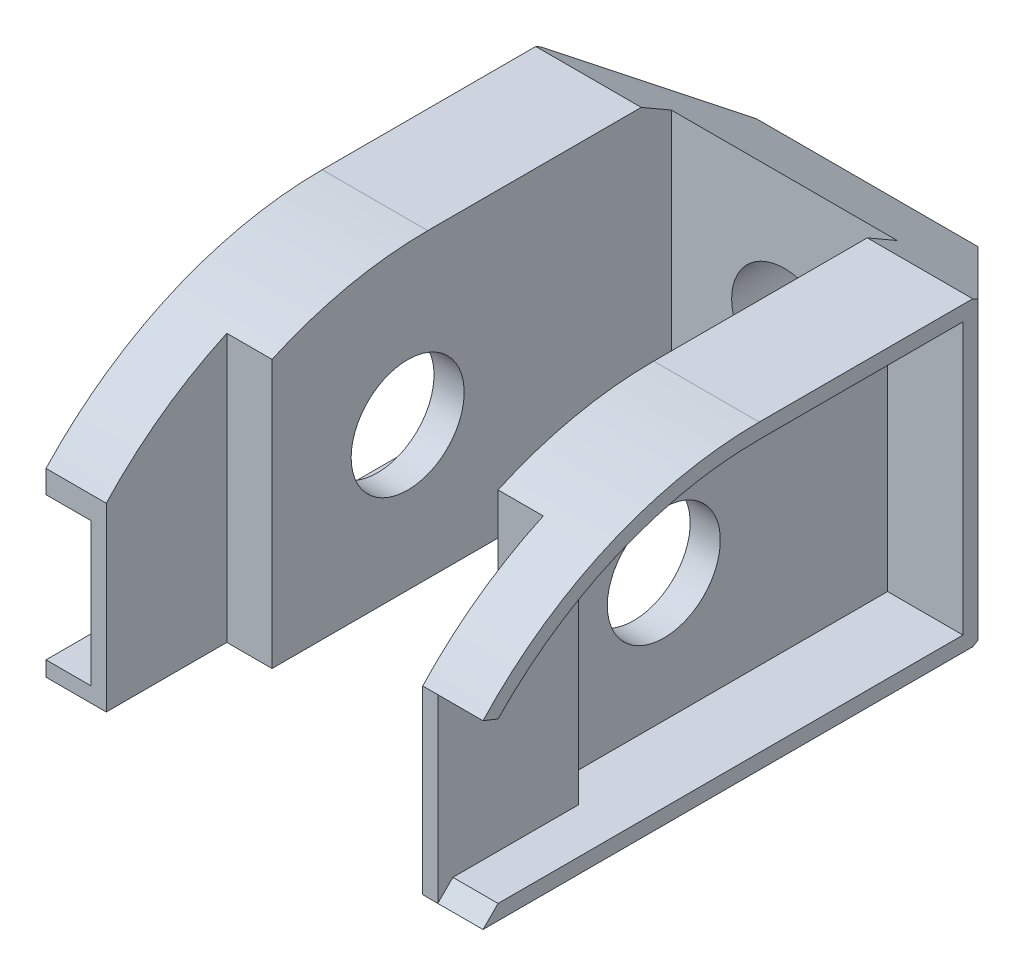
SolidWorks part; units mm, degrees
material "1060 Alloy"
ref_plane "Front Plane" through (0, 0, 0) normal (0, 0, 1) x (1, 0, 0)
ref_plane "Top Plane" through (0, 0, 0) normal (0, 1, 0) x (1, 0, 0)
ref_plane "Right Plane" through (0, 0, 0) normal (1, 0, 0) x (0, 0, -1)
sketch "Sketch1" plane through (0, 0, 0) normal (1, 0, 0) x (0, 0, -1)
  line L0 (0, 0) -> (65, 0)
  line L1 (0, 0) -> (0, 24)
  line L2 (65, 0) -> (80, 8.6603)
  line L3 (80, 8.6603) -> (80, 31.3397)
  line L4 (80, 31.3397) -> (65, 40)
  line L5 (65, 40) -> (36.6606, 40)
  arc A0 (36.6606, 40) -> (0, 24) centre (36.6606, -10) ccw
  circle A1 centre (34, 19) radius 7.5
  dimension "D7" = 50
  dimension "D9" = 15
  dimension "D1" = 65
  dimension "D2" = 24
  dimension "D3" = 15
  dimension "D4" = 30
  dimension "D5" = 15
  dimension "D6" = 30
  dimension "D8" = 40
  dimension "D10" = 19
  dimension "D11" = 31
extrude "Boss-Extrude1" add sketch "Sketch1" along normal blind 58
sketch "Sketch3" plane through (0, 0, 0) normal (0, 1, 0) x (1, 0, 0)
  line L0 (29, 80.0246) -> (29, 0.0246) construction
  line L3 (58, 0) -> (0, 0) construction
  line L4 (0, 36.6606) -> (0, 0) construction
  line L5 (58, 0) -> (58, 36.6606) construction
  line L6 (58, 65) -> (58, 36.6606) construction
  line L7 (58, 36.6606) -> (0, 36.6606) construction
  line L8 (0, 65) -> (0, 36.6606) construction
  line L9 (58, 65) -> (0, 65) construction
  line L10 (0, 80) -> (0, 65) construction
  line L11 (58, 80) -> (0, 80) construction
  line L12 (58, 0) -> (0, 0)
  line L13 (0, 36.6606) -> (0, 0)
  line L14 (58, 0) -> (58, 36.6606)
  line L15 (58, 65) -> (58, 36.6606)
  line L16 (58, 36.6606) -> (0, 36.6606)
  line L17 (0, 65) -> (0, 36.6606)
  line L18 (58, 65) -> (0, 65)
  line L19 (0, 80) -> (0, 65)
  line L20 (58, 80) -> (0, 80)
  line L22 (14, 69) -> (44, 69)
  line L23 (14, 69) -> (14, 16)
  line L24 (14, 16) -> (44, 16)
  line L25 (44, 69) -> (44, 16)
  line L26 (14, 69) -> (44, 16) construction
  line L27 (14, 16) -> (44, 69) construction
  point P4 (29, 42.5)
  dimension "D1" = 11
  dimension "D2" = 16
  dimension "D3" = 16
  dimension "D4" = 14
  dimension "D5" = 14
extrude "Cut-Extrude1" cut sketch "Sketch3" against normal blind 10 and the other way through all contours L25 L24 L23 L22
sketch "Sketch5" plane through (0, 0, 0) normal (0, 1, 0) x (1, 0, 0)
  line L0 (29, 80) -> (29, 0) construction
  line L1 (58, 80) -> (0, 80) construction
  line L2 (58, 0) -> (0, 0) construction
  line L3 (58, 65) -> (58, 36.6606) construction
  line L5 (44, 36.6606) -> (44, 16) construction
  line L6 (44, 65) -> (44, 36.6606) construction
  line L7 (58, 36.6606) -> (44, 36.6606) construction
  line L9 (14, 16) -> (14, 36.6606) construction
  line L10 (0, 36.6606) -> (0, 0) construction
  line L11 (14, 36.6606) -> (0, 36.6606) construction
  line L12 (0, 65) -> (0, 36.6606) construction
  line L13 (14, 65) -> (14, 36.6606) construction
  line L14 (14, 69) -> (14, 65) construction
  line L15 (44, 69) -> (44, 65) construction
  line L16 (58, 65) -> (44, 65) construction
  line L17 (58, 80) -> (58, 65) construction
  line L18 (0, 80) -> (0, 65) construction
  line L19 (14, 65) -> (0, 65) construction
  line L20 (14, 69) -> (44, 69) construction
  line L21 (58, 65) -> (58, 36.6606)
  line L22 (58, 16) -> (58, 0)
  line L23 (44, 36.6606) -> (44, 16)
  line L24 (44, 65) -> (44, 36.6606)
  line L25 (58, 36.6606) -> (44, 36.6606)
  line L26 (8, 16) -> (44, 16)
  line L27 (14, 16) -> (14, 36.6606)
  line L28 (0, 36.6606) -> (0, 0)
  line L29 (50, 16) -> (58, 16)
  line L30 (14, 36.6606) -> (0, 36.6606)
  line L31 (0, 65) -> (0, 36.6606)
  line L32 (14, 65) -> (14, 36.6606)
  line L33 (14, 69) -> (14, 65)
  line L34 (44, 69) -> (44, 65)
  line L35 (58, 65) -> (44, 65)
  line L36 (58, 80) -> (58, 65)
  line L37 (0, 80) -> (0, 65)
  line L38 (14, 65) -> (0, 65)
  line L39 (14, 69) -> (44, 69)
  line L40 (58, 80) -> (0, 80)
  line L41 (58, 0) -> (50, 0)
  line L42 (50, 0) -> (50, 16)
  line L43 (50, 16) -> (44, 16)
  line L44 (50, 0) -> (58, 0)
  line L45 (58, 16) -> (58, 0)
  line L46 (0, 16) -> (0, 0)
  line L47 (0, 0) -> (8, 0)
  line L48 (8, 0) -> (8, 16)
  line L49 (8, 16) -> (0, 16)
  line L50 (8, 0) -> (50, 0)
  dimension "D1" = 8
  dimension "D2" = 6
  dimension "D3" = 16
extrude "Cut-Extrude3" cut sketch "Sketch5" against normal through all and the other way up to next contours L0 L26 L48 L50 | L26 L0 L50 L42 L43
sketch "Sketch7" plane through (0, 0, 0) normal (0, 1, 0) x (1, 0, 0)
  line L0 (29, 80) -> (29, 69) construction
  line L1 (0, 65) -> (0, 36.6606) construction
  line L2 (58, 80) -> (0, 80) construction
  line L3 (14, 69) -> (44, 69) construction
  line L4 (0, 65.6967) -> (14.3033, 80)
  line L5 (0, 80) -> (0, 65) construction
  line L6 (14.3033, 80) -> (0, 80)
  line L7 (0, 80) -> (0, 65.6967)
  line L8 (58, 65.6967) -> (43.6967, 80)
  line L9 (43.6967, 80) -> (58, 80)
  line L10 (58, 80) -> (58, 65.6967)
  dimension "D1" = 45
  dimension "D2" = 14.3033
extrude "Cut-Extrude4" cut sketch "Sketch7" along normal through all contours L7 L4 L6 | L8 L9 L10
sketch "Sketch8" plane through (0, 0, -80) normal (0, 0, -1) x (-1, 0, 0)
  line L0 (-29, 31.3397) -> (-29, 8.6603) construction
  line L1 (-43.6967, 31.3397) -> (-14.3033, 31.3397) construction
  line L2 (-43.6967, 8.6603) -> (-14.3033, 8.6603) construction
  circle A1 centre (-29, 20) radius 7
  dimension "D1" = 14
extrude "Cut-Extrude5" cut sketch "Sketch8" against normal through all
sketch "Sketch10" plane through (0, 0, 0) normal (-1, 0, 0) x (0, 0, 1)
  line L8 (-63.6967, 39.5978) -> (-63.6967, 0.4022)
  line L9 (-63.6967, 38) -> (-63.6967, 2)
  line L34 (-65, 38) -> (-36.6606, 38)
  line L35 (-63.6967, 38) -> (-36.6606, 38)
  line L37 (0, 2) -> (-65, 2)
  line L38 (0, 2) -> (-63.6967, 2)
  line L39 (0, 24) -> (0, 0) construction
  line L40 (0, 20.9839) -> (0, 24)
  line L41 (0, 2) -> (0, 0)
  line L42 (0, 0) -> (-65, 0)
  line L43 (-65, 0) -> (-65.6967, 0.4022)
  line L44 (-65.6967, 0.4022) -> (-65.6967, 39.5978)
  line L45 (-65.6967, 39.5978) -> (-65, 40)
  line L46 (-65, 40) -> (-36.6606, 40)
  line L47 (0, 20.9839) -> (0, 2)
  arc A13 (-36.6606, 40) -> (0, 24) centre (-36.6606, -10) cw
  arc A14 (-1.4664, 22.64) -> (-36.6606, 38) centre (-36.6606, -10) ccw
  arc A15 (0, 20.9839) -> (-36.6606, 38) centre (-36.6606, -10) ccw
  circle M13 centre (-34, 19) radius 7.5
  line M17 (0, 0) -> (0, 24)
  dimension "D1" = 2
  dimension "D2" = 2
  dimension "D3" = 2
  dimension "D4" = 2
extrude "Cut-Extrude6" cut sketch "Sketch10" against normal blind 6 contours A15 L35 L9 L38 M17 M13
sketch "Sketch11" plane through (6, 0, 0) normal (-1, 0, 0) x (0, 0, 1)
  line L3 (-63.6967, 2) -> (-63.6967, 38)
  line L6 (-18.6967, 34.5118) -> (-18.6967, 2)
  line L7 (0, 2) -> (-63.6967, 2) construction
  line L8 (-18.6967, 2) -> (-63.6967, 2)
  line L9 (-63.6967, 38) -> (-36.6606, 38)
  arc A0 (0, 20.9839) -> (-36.6606, 38) centre (-36.6606, -10) ccw construction
  arc A1 (-36.6606, 38) -> (-18.6967, 34.5118) centre (-36.6606, -10) cw
  dimension "D1" = 45
extrude "Cut-Extrude7" cut sketch "Sketch11" against normal blind 4
sketch "Sketch12" plane through (58, 0, 0) normal (1, 0, 0) x (0, 0, -1)
  line L6 (0, 24) -> (2, 23.2061)
  line L7 (36.6606, 40) -> (65, 40)
  line L8 (65, 40) -> (36.6606, 40) construction
  line L10 (65.6967, 39.5978) -> (65.6967, 0.4022)
  line L11 (65.6967, 0.4022) -> (65, 0)
  line L12 (63.6967, 2) -> (63.6967, 38)
  line L13 (63.6967, 38) -> (36.6606, 38)
  line L14 (2, 23.2061) -> (2, 2)
  line L15 (2, 2) -> (63.6967, 2)
  line L16 (63.6967, 2) -> (63.6967, 38)
  line L17 (63.6967, 38) -> (36.6606, 38)
  line L19 (2, 2) -> (63.6967, 2)
  line L20 (65, 0) -> (0, 0)
  line L21 (0, 0) -> (0, 24)
  line L22 (65, 40) -> (65.6967, 39.5978)
  line L23 (2, 2) -> (0, 0)
  arc A1 (0, 24) -> (36.6606, 40) centre (36.6606, -10) cw
  arc A2 (36.6606, 38) -> (2, 23.2061) centre (36.6606, -10) ccw
  arc A3 (36.6606, 38) -> (2, 23.2061) centre (36.6606, -10) ccw
  line M17 (0, 24) -> (0, 0)
  circle M20 centre (34, 19) radius 7.5
  dimension "D2" = 210
  dimension "D1" = 2
extrude "Cut-Extrude9" cut sketch "Sketch12" against normal blind 6 contours L17 A3 L6 L23 L19 L16 M17 M20
sketch "Sketch13" plane through (52, 0, 0) normal (1, 0, 0) x (0, 0, -1)
  line L0 (18.6967, 34.5118) -> (18.6967, 2)
  line L2 (2, 2) -> (63.6967, 2) construction
  line L3 (18.6967, 2) -> (63.6967, 2)
  line L4 (63.6967, 2) -> (63.6967, 38)
  line L5 (63.6967, 38) -> (36.6606, 38)
  arc A0 (36.6606, 38) -> (18.6967, 34.5118) centre (36.6606, -10) ccw
  arc A1 (36.6606, 38) -> (2, 23.2061) centre (36.6606, -10) ccw construction
  dimension "D1" = 45
extrude "Cut-Extrude10" cut sketch "Sketch13" against normal blind 4 contours L0 L3 L4 L5 A0
equation "\"A\"= 58.00mm"
equation "\"B\"= 40.00mm"
equation "\"C\"= 65.00mm"
equation "\"D1@Sketch1\"=\"C\""
equation "\"D8@Sketch1\"=\"B\""
